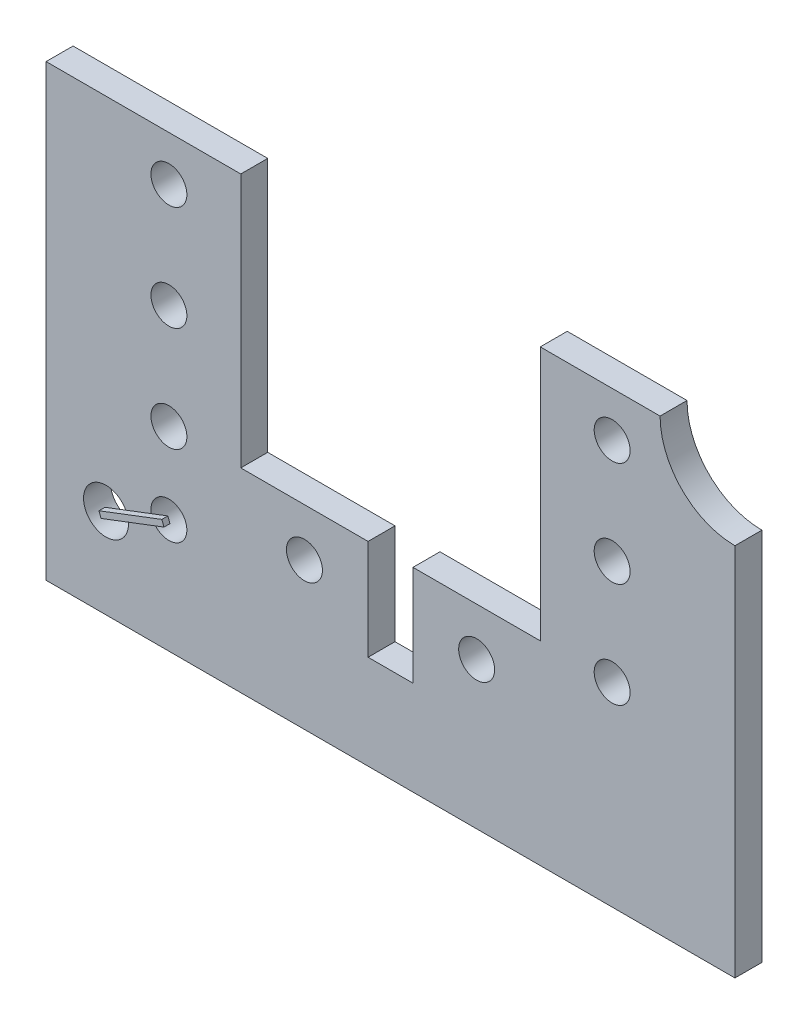
SolidWorks part; units mm, degrees
ref_plane "Спереди" through (0, 0, 0) normal (0, 0, 1) x (1, 0, 0)
ref_plane "Сверху" through (0, 0, 0) normal (0, 1, 0) x (1, 0, 0)
ref_plane "Справа" through (0, 0, 0) normal (1, 0, 0) x (0, 0, -1)
sketch "Эскиз1" plane through (0, 0, 0) normal (0, 0, 1) x (1, 0, 0)
  line L0 (-11.5, -18.5) -> (11.5, -18.5)
  line L1 (-11.5, -18.5) -> (-11.5, -6)
  line L3 (-5, -3.5) -> (-5, -12)
  line L4 (-5, -12) -> (5, -12)
  line L5 (0, 0) -> (0, -18.5) construction
  line L6 (5, -3.5) -> (5, -12)
  line L8 (11.5, -18.5) -> (11.5, -6)
  line L9 (5, -3.5) -> (9, -3.5)
  line L10 (-5, -2) -> (-5, -10.5) construction
  line L11 (-3.5, -12) -> (3.5, -12) construction
  line L12 (-9, -3.5) -> (-11.5, -3.5)
  line L13 (-11.5, -3.5) -> (-11.5, -6)
  line L14 (-5, -3.5) -> (-9, -3.5)
  line L16 (-9, -3.5) -> (-9, -2.3761) construction
  line L18 (-11.5, -6) -> (-13.5487, -6) construction
  arc A0 (-9, -3.5) -> (-11.5, -6) centre (-11.5, -3.5) cw construction
  arc A1 (9, -3.5) -> (11.5, -6) centre (11.5, -3.5) ccw
  point P12 (0, -12)
  point P20 (-14, -3)
  dimension "D1" = 0.5
  dimension "D2" = 4
  dimension "D3" = 23
  dimension "D4" = 15
extrude "Бобышка-Вытянуть1" add sketch "Эскиз1" along normal mid plane 0.9
sketch "Эскиз2" plane through (0, 0, 0) normal (0, 0, 1) x (1, 0, 0)
  line L1 (-0.75, -15.25) -> (0.75, -15.25) construction
  line L2 (-0.75, -15.25) -> (-0.75, -12)
  line L3 (-0.75, -12) -> (0.75, -12)
  line L4 (0.75, -15.25) -> (0.75, -12)
  line L5 (0, -18.5) -> (0, -15.25) construction
  line L6 (-0.75, -15.25) -> (-0.75, -15.35)
  line L11 (-0.75, -15.35) -> (0.75, -15.35)
  line L12 (0, -15.25) -> (0, -12) construction
  line L13 (5, -12) -> (-5, -12) construction
  line L14 (0, -12) -> (0, 0) construction
  line L15 (0.75, -15.35) -> (0.75, -15.25)
  line L16 (-11.5, -18.5) -> (11.5, -18.5) construction
  dimension "D1" = 1.5
  dimension "D2" = 0.1
extrude "Вырез-Вытянуть1" cut sketch "Эскиз2" against normal mid plane 10
sketch "Эскиз3" plane through (0, 0, 0) normal (0, 0, 1) x (1, 0, 0)
  line L1 (0, 0) -> (0, -14) construction
  line L2 (7, -3.5) -> (7, -12)
  line L3 (7, -3.5) -> (7, -12) construction
  line L5 (0, -14) -> (7, -14) construction
  line L6 (5, -12) -> (0.75, -12) construction
  line L7 (3.5, -14) -> (3.5, -12) construction
  line L8 (-7, -14) -> (-4.6667, -14) construction
  line L9 (-4.6667, -14) -> (-2.3333, -14) construction
  circle A0 centre (7, -5) radius 0.5
  circle A3 centre (7, -8) radius 0.5
  circle A4 centre (7, -11) radius 0.5
  circle A5 centre (7, -14) radius 0.5
  circle A6 centre (-7, -14) radius 0.5
  circle A7 centre (-7, -11) radius 0.5
  circle A8 centre (-7, -8) radius 0.5
  circle A9 centre (-7, -5) radius 0.5
  circle A10 centre (4.6667, -14) radius 0.5
  circle A11 centre (-4.6667, -14) radius 0.5
  circle A13 centre (2.3333, -14) radius 0.5
  circle A14 centre (-2.3333, -14) radius 0.5
  point P10 (7, -4.5)
  dimension "D5" = 1
  dimension "D3" = 1
  dimension "D4" = 2
  dimension "D1" = 2
  dimension "D2" = 4
extrude "Вырез-Вытянуть2" [suppressed] cut sketch "Эскиз3" against normal mid plane 10
sketch "Эскиз4" plane through (0, 0, 0) normal (0, 0, 1) x (1, 0, 0)
  line L0 (-11.5, -18.5) -> (11.5, -18.5) construction
  line L1 (-11.5, -3.5) -> (-11.5, -18.5) construction
  line L2 (-2.875, -13.6) -> (-0.75, -13.6) construction
  line L3 (0.75, -12) -> (0.75, -15.35) construction
  line L4 (-2.875, -13) -> (-2.875, -12) construction
  line L5 (-7.4, -12) -> (-7.4, -14.7) construction
  line L6 (-0.75, -12) -> (-5, -12) construction
  line L7 (-0.75, -15.35) -> (-0.75, -12) construction
  line L8 (-7.4, -15.3) -> (-7.4, -18.5) construction
  line L9 (-5, -12) -> (-7.4, -12) construction
  line L10 (-7.4, -12) -> (-7.4, -8.5) construction
  line L11 (-7.4, -8.5) -> (-7.4, -5) construction
  line L12 (-7.4, -5) -> (-7.4, -3.5) construction
  line L13 (-5, -3.5) -> (-11.5, -3.5) construction
  line L14 (0, -50) -> (0, 50) construction
  line L15 (0, -18.5) -> (0, -17.6492) construction
  line L16 (7.4, -5) -> (7.4, -3.5) construction
  line L18 (-6.8, -5) -> (-5, -5) construction
  line L19 (-5, -12) -> (-5, -3.5) construction
  circle A0 centre (-9.5, -15.5) radius 0.75
  circle A2 centre (-2.875, -13.6) radius 0.6
  circle A3 centre (-7.4, -14.7) radius 0.6
  circle A5 centre (-7.4, -8.5) radius 0.6
  circle A6 centre (-7.4, -5) radius 0.6
  circle A7 centre (7.4, -8.5) radius 0.6
  circle A8 centre (7.4, -5) radius 0.6
  circle A9 centre (2.875, -13.6) radius 0.6
  circle A10 centre (-7.4, -12) radius 0.6
  circle A11 centre (7.4, -12) radius 0.6
  point P6 (0.75, -13.675)
  point P23 (-2.875, -13)
  point P47 (-7.4, -14.1)
  point P48 (-7.4, -12.6)
  dimension "D3" = 1.5
  dimension "D4" = 1.2
  dimension "D1" = 3
  dimension "D2" = 2
  dimension "D5" = 1.5
  dimension "D6" = 1.5
  dimension "D7" = 1
  dimension "D8" = 1.8
extrude "Вырез-Вытянуть3" cut sketch "Эскиз4" against normal mid plane 10 contours A0
sketch "Эскиз5" plane through (0, 0, 0.45) normal (0, 0, -1) x (-1, 0, 0)
  line L0 (9.5, -15.5) -> (7.4, -14.7)
extrude "Вытянуть-Тонкостенный1" add sketch "Эскиз5" against normal blind 0.2 thin thin type mid plane wall 0.2
sketch "Эскиз6" plane through (0, 0, -0.45) normal (0, 0, -1) x (-1, 0, 0)
  line L0 (2.875, -13.6) -> (7.4, -14.7)
  line L1 (7.3644, -14.7934) -> (7.4356, -14.6066) construction
extrude "Вытянуть-Тонкостенный2" add sketch "Эскиз6" along normal blind 0.2 thin thin type mid plane wall 0.23
